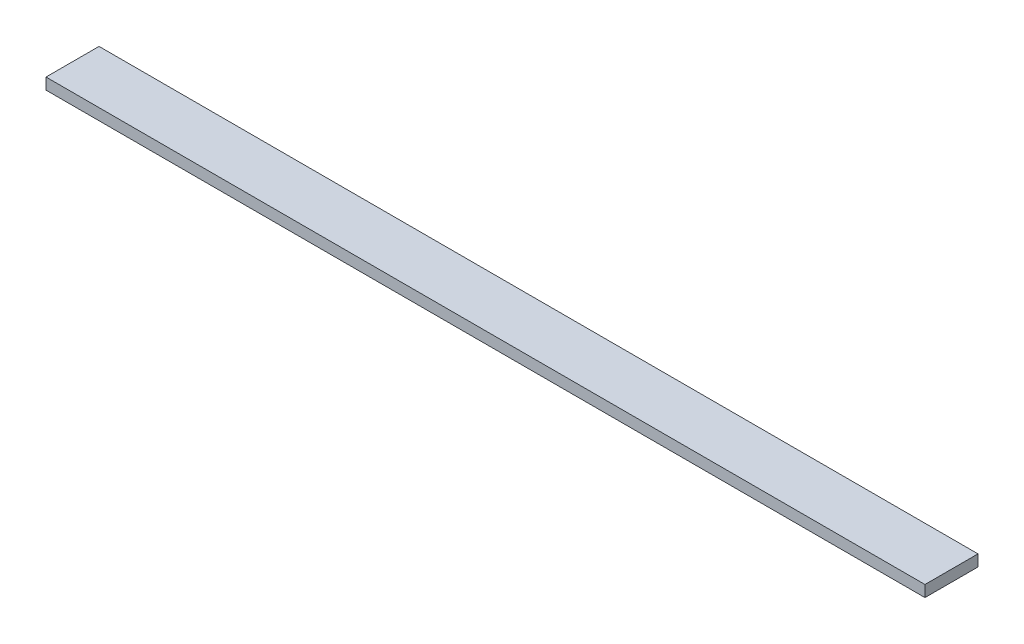
SolidWorks part; units mm, degrees
ref_plane "Front Plane" through (0, 0, 0) normal (0, 0, 1) x (1, 0, 0)
ref_plane "Top Plane" through (0, 0, 0) normal (0, 1, 0) x (1, 0, 0)
ref_plane "Right Plane" through (0, 0, 0) normal (1, 0, 0) x (0, 0, -1)
other "Configuration Table"
sketch "Sketch1" plane through (0, 0, 0) normal (0, 0, 1) x (1, 0, 0)
  line L1 (60, 140) -> (640, 140)
  line L2 (60, 140) -> (60, 147.5)
  line L3 (60, 147.5) -> (640, 147.5)
  line L4 (640, 140) -> (640, 147.5)
extrude "PACK_pano_klemens_rayi_1" add sketch "Sketch1" against normal blind 35 from offset 213 separate body
